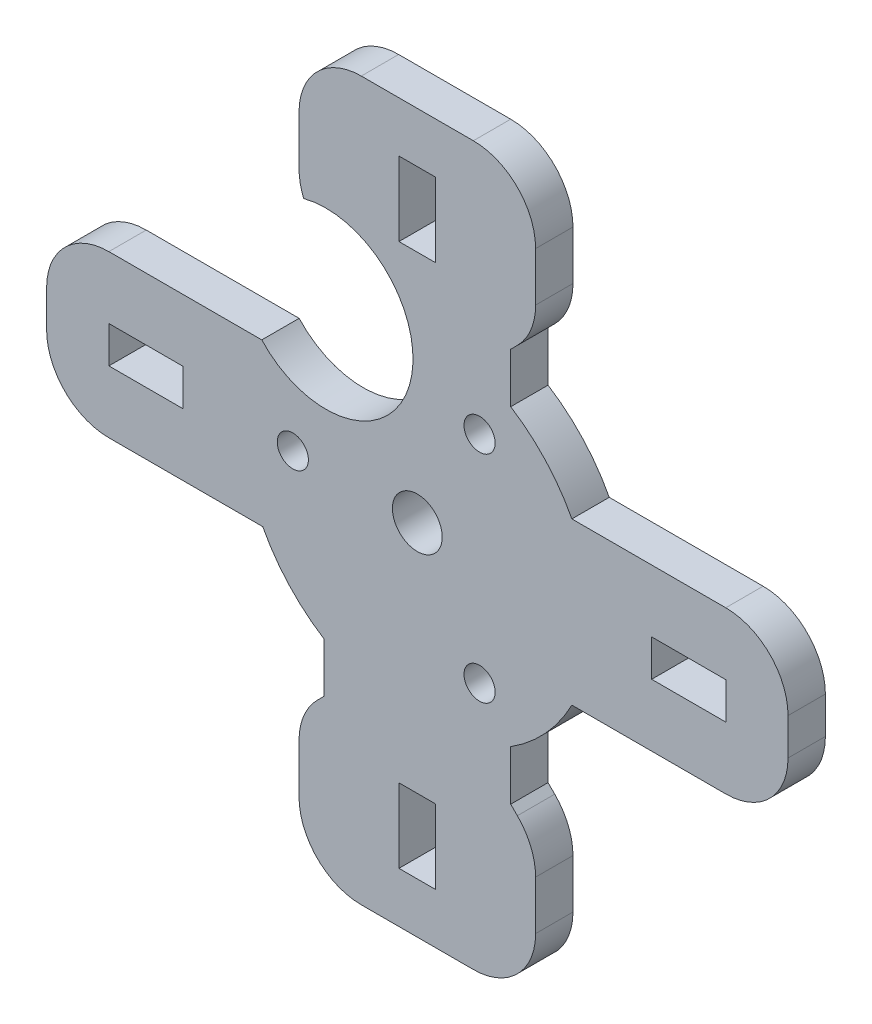
SolidWorks part; units mm, degrees
ref_plane "Front Plane" through (0, 0, 0) normal (0, 0, 1) x (1, 0, 0)
ref_plane "Top Plane" through (0, 0, 0) normal (0, 1, 0) x (1, 0, 0)
ref_plane "Right Plane" through (0, 0, 0) normal (1, 0, 0) x (0, 0, -1)
sketch "Sketch1" plane through (0, 0, 0) normal (0, 0, 1) x (1, 0, 0)
  line L0 (-14, 0) -> (14, 0) construction
  line L1 (7.5, 18.8216) -> (9.5, 18.8216)
  line L2 (-7.5, -18.8216) -> (7.5, -18.8216)
  line L3 (-7.5, -18.8216) -> (-7.5, 18.8216) construction
  line L4 (-7.5, 18.8216) -> (7.5, 18.8216)
  line L5 (7.5, -18.8216) -> (7.5, 18.8216) construction
  line L6 (-7.5, -18.8216) -> (7.5, 18.8216) construction
  line L7 (-7.5, 18.8216) -> (7.5, -18.8216) construction
  line L8 (9.5, 18.8216) -> (9.5, 17.8216)
  line L9 (9.5, 17.8216) -> (7.5, 15.8216)
  line L10 (7.5, 15.8216) -> (-7.5, 15.8216) construction
  line L11 (-7.5, 15.8216) -> (-9.5, 17.8216)
  line L12 (-9.5, 17.8216) -> (-9.5, 18.8216)
  line L13 (-9.5, 18.8216) -> (-7.5, 18.8216)
  line L14 (-9.5, 17.8216) -> (9.5, 17.8216) construction
  line L15 (-7.5, 15.8216) -> (-7.5, 11.8216)
  line L16 (7.5, 15.8216) -> (7.5, 11.8216)
  line L17 (7.5, -15.8216) -> (-7.5, -15.8216) construction
  line L18 (-9.5, -17.8216) -> (9.5, -17.8216) construction
  line L19 (7.5, -15.8216) -> (7.5, -11.8216)
  line L20 (9.5, -17.8216) -> (7.5, -15.8216)
  line L21 (9.5, -18.8216) -> (9.5, -17.8216)
  line L22 (7.5, -18.8216) -> (9.5, -18.8216)
  line L23 (-9.5, -18.8216) -> (-7.5, -18.8216)
  line L24 (-9.5, -17.8216) -> (-9.5, -18.8216)
  line L25 (-7.5, -15.8216) -> (-9.5, -17.8216)
  line L26 (-7.5, -15.8216) -> (-7.5, -11.8216)
  arc A0 (-7.5, 11.8216) -> (-7.5, -11.8216) centre (0, 0) ccw
  circle A1 centre (-10, 0) radius 1.25
  circle A2 centre (5, 8.6603) radius 1.25
  circle A3 centre (0, 0) radius 10 construction
  arc A4 (7.5, -11.8216) -> (7.5, 11.8216) centre (0, 0) ccw
  circle A5 centre (5, -8.6603) radius 1.25
  point P34 (0, 0)
  dimension "D1" = 28
  dimension "D2" = 20
  dimension "D9" = 2.5
  dimension "D10" = 3
  dimension "D3" = 15
  dimension "D4" = 4
  dimension "D5" = 1
  dimension "D6" = 45
  dimension "D7" = 45
  dimension "D8" = 2
extrude "Boss-Extrude1" add sketch "Sketch1" along normal blind 3
sketch "Sketch2" plane through (0, 0, 0) normal (0, 0, -1) x (-1, 0, 0)
  line L0 (9.5, 18.8216) -> (-9.5, 18.8216)
  line L1 (9.5, 18.8216) -> (9.5, 28.8216)
  line L2 (-9.5, 18.8216) -> (-9.5, 28.8216)
  line L3 (9.5, 28.8216) -> (-9.5, 28.8216)
  line L4 (9.5, -18.8216) -> (-9.5, -18.8216)
  line L5 (9.5, -18.8216) -> (9.5, -28.8216)
  line L6 (-9.5, -18.8216) -> (-9.5, -28.8216)
  line L7 (9.5, -28.8216) -> (-9.5, -28.8216)
  dimension "D2" = 10
  dimension "D3" = 10
extrude "Boss-Extrude2" add sketch "Sketch2" against normal up to vertex (3 mm away) up to point (-9.5, 17.8216, 3)
sketch "Sketch3" plane through (0, 0, 0) normal (0, 0, -1) x (-1, 0, 0)
  circle A0 centre (0, 0) radius 2
  dimension "D1" = 4
extrude "Cut-Extrude1" cut sketch "Sketch3" against normal blind 10
sketch "Sketch4" plane through (0, 0, 0) normal (0, 0, -1) x (-1, 0, 0)
  line L0 (0, 28.8216) -> (0, -28.8216) construction
  line L1 (9.5, 28.8216) -> (-9.5, 28.8216) construction
  line L2 (-9.5, -28.8216) -> (9.5, -28.8216) construction
  line L4 (1.475, 24.7716) -> (-1.475, 24.7716)
  line L5 (1.475, 24.7716) -> (1.475, 18.8216)
  line L6 (1.475, 18.8216) -> (-1.475, 18.8216)
  line L7 (-1.475, 24.7716) -> (-1.475, 18.8216)
  line L8 (1.475, 24.7716) -> (-1.475, 18.8216) construction
  line L9 (1.475, 18.8216) -> (-1.475, 24.7716) construction
  line L10 (1.475, -18.8216) -> (-1.475, -18.8216)
  line L11 (1.475, -18.8216) -> (1.475, -24.7716)
  line L12 (1.475, -24.7716) -> (-1.475, -24.7716)
  line L13 (-1.475, -18.8216) -> (-1.475, -24.7716)
  line L14 (1.475, -18.8216) -> (-1.475, -24.7716) construction
  line L15 (1.475, -24.7716) -> (-1.475, -18.8216) construction
  point P6 (0, 21.7966)
  point P11 (0, -21.7966)
  dimension "D1" = 2.95
  dimension "D3" = 5.95
  dimension "D4" = 5.95
  dimension "D5" = 1
  dimension "D6" = 1
extrude "Cut-Extrude2" cut sketch "Sketch4" against normal through all
fillet "Fillet1" radius 5 8 edges at (9.5, -28.8216, 1.5) (9.5, 28.8216, 1.5) (-9.5, -28.8216, 1.5) (-9.5, 28.8216, 1.5) (9.5, 17.8216, 1.5) (9.5, -17.8216, 1.5) (-9.5, -17.8216, 1.5) (-9.5, 17.8216, 1.5)
sketch "Sketch5" plane through (0, 0, 0) normal (0, 0, -1) x (-1, 0, 0)
  line L0 (0, 0) -> (-21.7966, 0) construction
  line L1 (0, 0) -> (21.7966, 0) construction
  line L3 (24.7716, 1.475) -> (18.8216, 1.475)
  line L4 (24.7716, 1.475) -> (24.7716, -1.475)
  line L5 (24.7716, -1.475) -> (18.8216, -1.475)
  line L6 (18.8216, 1.475) -> (18.8216, -1.475)
  line L7 (24.7716, 1.475) -> (18.8216, -1.475) construction
  line L8 (24.7716, -1.475) -> (18.8216, 1.475) construction
  line L9 (-18.8216, 1.475) -> (-24.7716, 1.475)
  line L10 (-18.8216, 1.475) -> (-18.8216, -1.475)
  line L11 (-18.8216, -1.475) -> (-24.7716, -1.475)
  line L12 (-24.7716, 1.475) -> (-24.7716, -1.475)
  line L13 (-18.8216, 1.475) -> (-24.7716, -1.475) construction
  line L14 (-18.8216, -1.475) -> (-24.7716, 1.475) construction
  line L15 (1.475, -18.8216) -> (-1.475, -18.8216) construction
  line L16 (-1.475, 18.8216) -> (1.475, 18.8216) construction
  line L17 (-1.475, -24.7716) -> (1.475, -24.7716) construction
  line L18 (-4.5, -28.8216) -> (4.5, -28.8216) construction
  line L19 (-12.4127, -6.475) -> (-29.7716, -6.475)
  line L20 (29.7716, 6.475) -> (12.4127, 6.475)
  line L21 (29.7716, 6.475) -> (29.7716, -6.475)
  line L22 (29.7716, -6.475) -> (12.4127, -6.475)
  line L23 (-29.7716, 6.475) -> (-29.7716, -6.475)
  line L24 (-12.4127, 6.475) -> (-29.7716, 6.475)
  arc A0 (-7.5, 11.8216) -> (-7.5, -11.8216) centre (0, 0) ccw construction
  arc A1 (7.5, -11.8216) -> (7.5, 11.8216) centre (0, 0) ccw construction
  arc A2 (-12.4127, 6.475) -> (-12.4127, -6.475) centre (0, 0) ccw
  arc A3 (12.4127, -6.475) -> (12.4127, 6.475) centre (0, 0) ccw
  point P24 (-29.7716, 0)
  dimension "D1" = 2.95
  dimension "D3" = 5.95
  dimension "D2" = 5.95
  dimension "D4" = 18.8216
  dimension "D5" = 18.8216
  dimension "D6" = 18.8216
  dimension "D7" = 18.8216
  dimension "D8" = 4.05
  dimension "D9" = 5
  dimension "D10" = 5
  dimension "D11" = 5
  dimension "D12" = 5
extrude "Boss-Extrude3" add sketch "Sketch5" against normal up to vertex (3 mm away)
fillet "Fillet2" radius 5 4 edges at (29.7716, 6.475, 1.5) (29.7716, -6.475, 1.5) (-29.7716, -6.475, 1.5) (-29.7716, 6.475, 1.5)
sketch "Sketch6" plane through (0, 0, 3) normal (0, 0, 1) x (1, 0, 0)
  circle A0 centre (-7.3462, 11.2207) radius 7
extrude "Cut-Extrude4" cut sketch "Sketch6" against normal blind 10
equation "\"D4@Sketch4\"=\"D3@Sketch4\""
equation "\"D6@Sketch4\"=\"D5@Sketch4\""
equation "\"D3@Sketch5\"=\"D2@Sketch5\""
equation "\"D6@Sketch5\"=\"D5@Sketch5\""
equation "\"D7@Sketch5\"=\"D5@Sketch5\""
